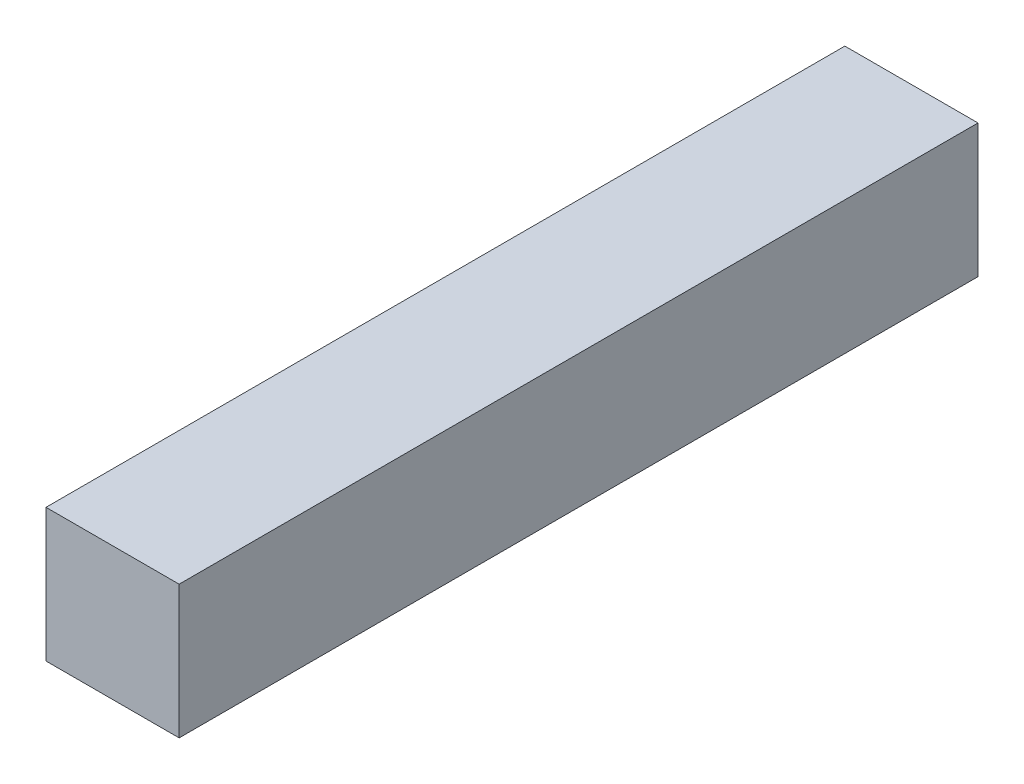
SolidWorks part; units mm, degrees
ref_plane "前基準面" through (0, 0, 0) normal (0, 0, 1) x (1, 0, 0)
ref_plane "上基準面" through (0, 0, 0) normal (0, 1, 0) x (1, 0, 0)
ref_plane "右基準面" through (0, 0, 0) normal (1, 0, 0) x (0, 0, -1)
sketch "草圖1" plane through (0, 0, 0) normal (0, 0, 1) x (1, 0, 0)
  line L1 (-10, 10) -> (10, 10)
  line L2 (-10, 10) -> (-10, -10)
  line L3 (-10, -10) -> (10, -10)
  line L4 (10, 10) -> (10, -10)
  point P4 (0, 10)
  point P6 (-10, 0)
  dimension "D1" = 20
  dimension "D2" = 20
extrude "填料-伸長1" add sketch "草圖1" along normal blind 120
sketch "草圖2" plane through (0, 10, 0) normal (0, 1, 0) x (1, 0, 0)
  line L2 (10, 0) -> (-10, 0) construction
  line L3 (10, -120) -> (-10, -120) construction
  line L4 (-10, -60) -> (10, -60) construction
  line L5 (-10, -120) -> (-10, 0) construction
  line L6 (10, -120) -> (10, 0) construction
  circle A0 centre (0, -10) radius 4
  circle A1 centre (0, -99) radius 4
  dimension "D1" = 8
  dimension "D3" = 8
  dimension "D2" = 10
  dimension "D4" = 21
  dimension "D5" = 50
  dimension "D6" = 39
